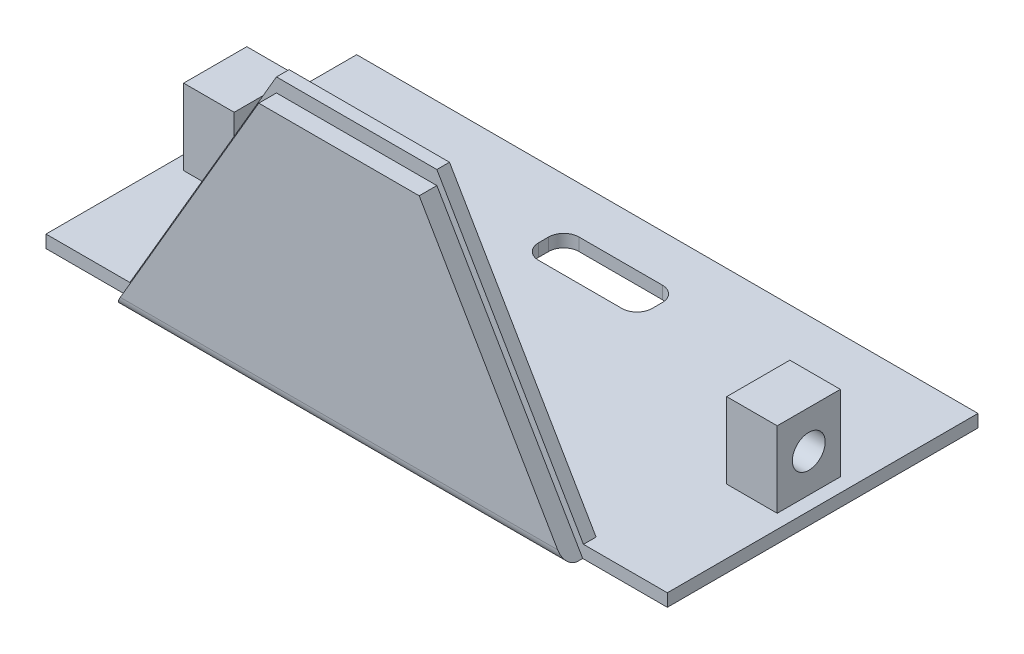
SolidWorks part; units mm, degrees
ref_plane "Ebene vorne" through (0, 0, 0) normal (0, 0, 1) x (1, 0, 0)
ref_plane "Ebene oben" through (0, 0, 0) normal (0, 1, 0) x (1, 0, 0)
ref_plane "Ebene rechts" through (0, 0, 0) normal (1, 0, 0) x (0, 0, -1)
sketch "Skizze1" plane through (0, 0, 0) normal (0, 1, 0) x (1, 0, 0)
  line L1 (24.6, 12.3) -> (-24.6, 12.3)
  line L2 (24.6, 12.3) -> (24.6, -12.3)
  line L3 (24.6, -12.3) -> (-24.6, -12.3)
  line L4 (-24.6, 12.3) -> (-24.6, -12.3)
  line L5 (24.6, 12.3) -> (-24.6, -12.3) construction
  line L6 (24.6, -12.3) -> (-24.6, 12.3) construction
  point P0 (0, 0)
  dimension "D1" = 24.6
  dimension "D2" = 49.2
extrude "Aufsatz-Linear austragen1" add sketch "Skizze1" along normal blind 1
sketch "Skizze2" plane through (0, 0, 12.3) normal (0, 0, 1) x (1, 0, 0)
  line L0 (0, 0) -> (0, 23.7746) construction
  line L1 (-24.6, 0) -> (24.6, 0) construction
  line L2 (17.9, 0) -> (-17.9, 0)
  line L3 (17.9, 0) -> (6.35, 19.8)
  line L4 (-17.9, 0) -> (-6.35, 19.8)
  line L5 (-6.35, 19.8) -> (6.35, 19.8)
  point P9 (0, 19.8)
  dimension "D1" = 17.9
  dimension "D3" = 19.8
  dimension "D4" = 6.35
extrude "Aufsatz-Linear austragen2" add sketch "Skizze2" along normal blind 1.4
sketch "Skizze4" plane through (0, 0, 12.3) normal (0, 0, -1) x (-1, 0, 0)
  line L0 (17.3167, 1) -> (-17.3167, 1) construction
  line L2 (-6.35, 19.8) -> (6.35, 19.8) construction
  line L3 (6.35, 19.8) -> (17.3167, 1) construction
  line L4 (6.35, 19.8) -> (6.35, 20.9) construction
  line L5 (6.35, 20.9) -> (17.9583, 1)
  line L6 (24.6, 1) -> (17.3167, 1) construction
  line L7 (0, 0) -> (0, 22.2284) construction
  line L8 (6.35, 20.9) -> (-6.35, 20.9)
  line L9 (17.9583, 1) -> (-17.9583, 1)
  line L10 (-6.35, 19.8) -> (-6.35, 20.9) construction
  line L11 (-6.35, 19.8) -> (-17.3167, 1) construction
  line L12 (-6.35, 20.9) -> (-17.9583, 1)
  point P17 (0, 20.9)
  point P19 (0, 19.8)
  point P20 (0, 1)
  dimension "D1" = 1.1
extrude "Aufsatz-Linear austragen3" add sketch "Skizze4" along normal blind 1
ref_plane "Ebene1" through (5, 0, 0) normal (1, 0, 0) x (0, 0, -1)
sketch "Skizze5" plane through (5, 0, 0) normal (1, 0, 0) x (0, 0, -1)
  line L0 (-6.3, 1) -> (-11.3, 15.9)
  line L1 (-12.3, 1) -> (12.3, 1) construction
  line L2 (-11.3, 20.9) -> (-11.3, 1) construction
  line L3 (-11.3, 20.9) -> (-12.3, 20.9) construction
  line L4 (-11.3, 15.9) -> (-11.3, 1)
  line L5 (-11.3, 1) -> (-6.3, 1)
  dimension "D1" = 5
  dimension "D2" = 5
extrude "Aufsatz-Linear austragen4" add sketch "Skizze5" along normal blind 0.5 and the other way blind 0.5
mirror "Spiegeln1" about plane through (0, 0, 0) normal (1, 0, 0) of "Aufsatz-Linear austragen4"
sketch "Skizze6" plane through (0, 1, 0) normal (0, 1, 0) x (1, 0, 0)
  line L0 (0, 0) -> (-23.3324, 0) construction
  line L1 (-24.6, 12.3) -> (-24.6, -12.3) construction
  line L2 (-19.5, 2.5) -> (-23.5, 2.5)
  line L3 (-19.5, 2.5) -> (-19.5, -2.5)
  line L4 (-19.5, -2.5) -> (-23.5, -2.5)
  line L5 (-23.5, 2.5) -> (-23.5, -2.5)
  line L6 (-19.5, 2.5) -> (-23.5, -2.5) construction
  line L7 (-19.5, -2.5) -> (-23.5, 2.5) construction
  point P3 (-21.5, 0)
  dimension "D1" = 5
  dimension "D2" = 4
  dimension "D3" = 1.1
extrude "Aufsatz-Linear austragen5" add sketch "Skizze6" along normal blind 6
sketch "Skizze7" plane through (-23.5, 0, 0) normal (-1, 0, 0) x (0, 0, 1)
  line L0 (-12.3, 1) -> (12.3, 1) construction
  line L1 (0, 0) -> (0, 4) construction
  circle A0 centre (0, 4) radius 1.3
  circle A1 centre (0, 4) radius 3 construction
  dimension "D1" = 2.6
  dimension "D2" = 3
extrude "Schnitt-Linear austragen1" cut sketch "Skizze7" against normal up to surface (4 mm away) up to face at (-19.5, 4, 0)
mirror "Spiegeln2" about plane through (0, 0, 0) normal (1, 0, 0) of "Schnitt-Linear austragen1", "Aufsatz-Linear austragen5"
fillet "Verrundung1" radius 1 1 edges at (0, 0, 13.7)
sketch "Skizze8" plane through (0, 0, 0) normal (0, -1, 0) x (1, 0, 0)
  line L0 (0, 0) -> (0, -7) construction
  line L1 (24.6, -12.3) -> (-24.6, -12.3) construction
  line L2 (3.3, -5.4) -> (-3.3, -5.4)
  line L3 (4.5, -6.6) -> (4.5, -7.4)
  line L4 (3.3, -8.6) -> (-3.3, -8.6)
  line L5 (-4.5, -6.6) -> (-4.5, -7.4)
  line L6 (4.5, -5.4) -> (-4.5, -8.6) construction
  line L7 (4.5, -8.6) -> (-4.5, -5.4) construction
  arc A0 (4.5, -7.4) -> (3.3, -8.6) centre (3.3, -7.4) cw
  arc A1 (-3.3, -8.6) -> (-4.5, -7.4) centre (-3.3, -7.4) cw
  arc A2 (3.3, -5.4) -> (4.5, -6.6) centre (3.3, -6.6) cw
  arc A3 (-3.3, -5.4) -> (-4.5, -6.6) centre (-3.3, -6.6) ccw
  point P19 (0, -7.1792)
  dimension "D3" = 1.2
  dimension "D1" = 9
  dimension "D2" = 3.2
  dimension "D4" = 3.7
extrude "Schnitt-Linear austragen2" cut sketch "Skizze8" against normal up to surface (1 mm away) up to face at (21.5, 1, 0)
